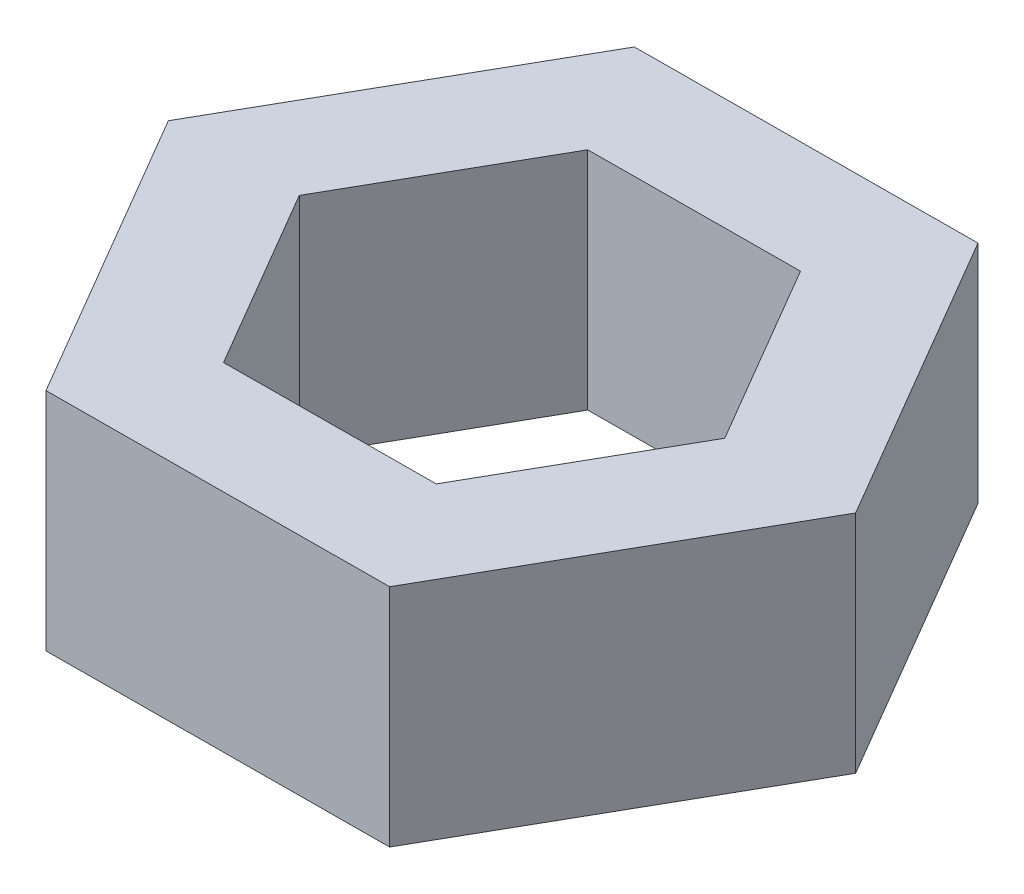
SolidWorks part; units mm, degrees
ref_plane "Alzado" through (0, 0, 0) normal (0, 0, 1) x (1, 0, 0)
ref_plane "Planta" through (0, 0, 0) normal (0, 1, 0) x (1, 0, 0)
ref_plane "Vista lateral" through (0, 0, 0) normal (1, 0, 0) x (0, 0, -1)
sketch "Croquis1" plane through (0, 0, 0) normal (0, 1, 0) x (1, 0, 0)
  line L0 (12.1242, 0.0703) -> (6.0012, 10.535)
  line L1 (3.7904, -6.4781) -> (7.5054, 0.0435)
  line L2 (7.5054, 0.0435) -> (3.715, 6.5216)
  line L3 (3.715, 6.5216) -> (-3.7904, 6.4781)
  line L4 (-3.7904, 6.4781) -> (-7.5054, -0.0435)
  line L5 (-7.5054, -0.0435) -> (-3.715, -6.5216)
  line L6 (-3.715, -6.5216) -> (3.7904, -6.4781)
  line L7 (6.0012, 10.535) -> (-6.1229, 10.4647)
  line L8 (-6.1229, 10.4647) -> (-12.1242, -0.0703)
  line L9 (-12.1242, -0.0703) -> (-6.0012, -10.535)
  line L10 (-6.0012, -10.535) -> (6.1229, -10.4647)
  line L11 (6.1229, -10.4647) -> (12.1242, 0.0703)
  circle A0 centre (0, 0) radius 6.5 construction
  dimension "D1" = 13
  dimension "D2" = 4
extrude "Saliente-Extruir1" add sketch "Croquis1" along normal blind 8
